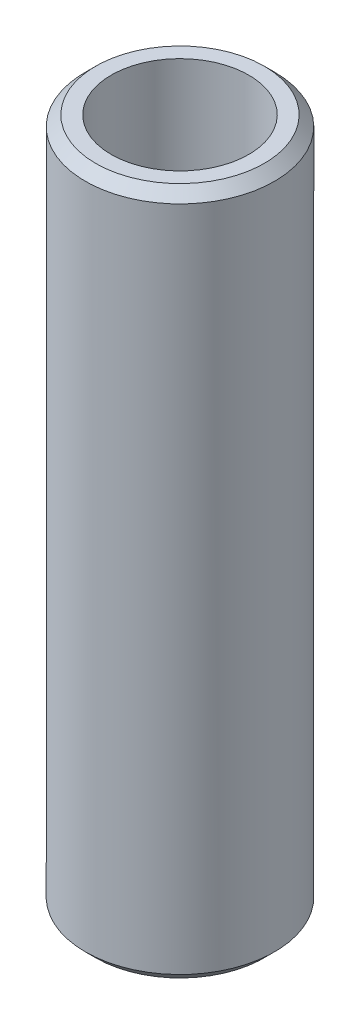
SolidWorks part; units mm, degrees
ref_plane "Alzado" through (0, 0, 0) normal (0, 0, 1) x (1, 0, 0)
ref_plane "Planta" through (0, 0, 0) normal (0, 1, 0) x (1, 0, 0)
ref_plane "Vista lateral" through (0, 0, 0) normal (1, 0, 0) x (0, 0, -1)
sketch "Croquis1" plane through (0, 0, 0) normal (0, 1, 0) x (1, 0, 0)
  circle A0 centre (0, 0) radius 2
  circle A1 centre (0, 0) radius 2.75
  dimension "D1" = 4
  dimension "D2" = 5.5
extrude "Saliente-Extruir1" add sketch "Croquis1" along normal blind 20
chamfer "Chaflán1" distance 0.3 angle 45 2 edges at (0, 0, 2.75) (0, 20, 2.75)
